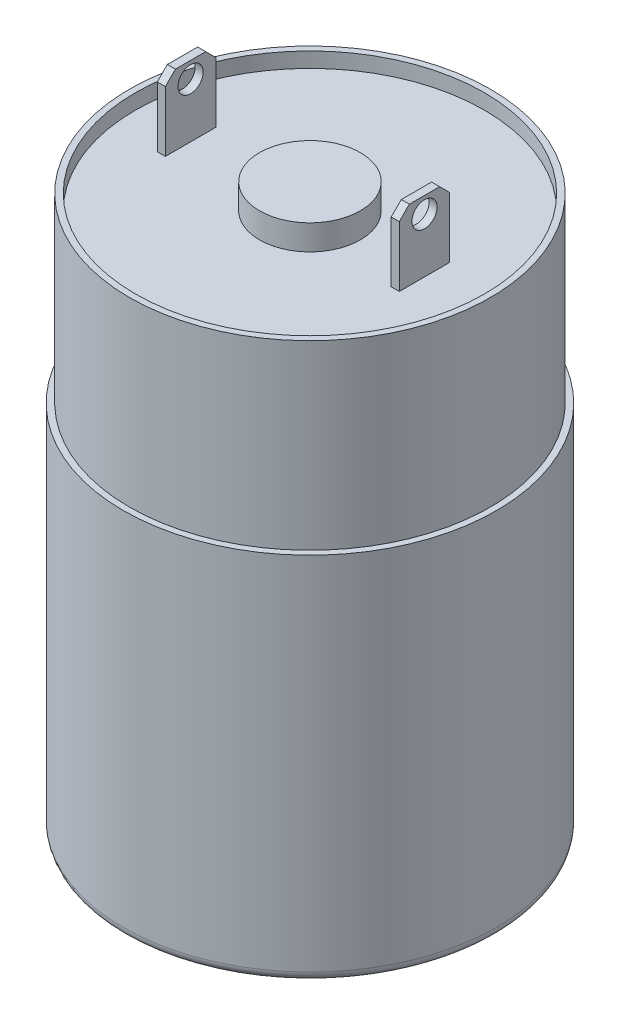
SolidWorks part; units mm, degrees
material "3.0205 (EN-AW 1200)"
ref_plane "Alzado" through (0, 0, 0) normal (0, 0, 1) x (1, 0, 0)
ref_plane "Planta" through (0, 0, 0) normal (0, 1, 0) x (1, 0, 0)
ref_plane "Vista lateral" through (0, 0, 0) normal (1, 0, 0) x (0, 0, -1)
sketch "Croquis1" plane through (0, 0, 0) normal (0, 1, 0) x (1, 0, 0)
  circle A0 centre (0, 0) radius 18.5
  dimension "D1" = 37
extrude "Saliente-Extruir1" add sketch "Croquis1" along normal mid plane 36.8
sketch "Croquis2" plane through (0, 18.4, 0) normal (0, 1, 0) x (1, 0, 0)
  circle A0 centre (0, 0) radius 17.9
  dimension "D1" = 35.8
extrude "Saliente-Extruir2" add sketch "Croquis2" along normal blind 18
sketch "Croquis3" plane through (0, 36.4, 0) normal (0, 1, 0) x (1, 0, 0)
  circle A0 centre (0, 0) radius 17.3
  dimension "D1" = 34.6
extrude "Cortar-Extruir1" cut sketch "Croquis3" against normal blind 1.5
sketch "Croquis4" plane through (0, 34.9, 0) normal (0, 1, 0) x (1, 0, 0)
  circle A0 centre (0, 0) radius 5
  dimension "D1" = 10
extrude "Saliente-Extruir3" add sketch "Croquis4" along normal blind 2.5
sketch "Croquis5" plane through (0, 34.9, 0) normal (0, 1, 0) x (1, 0, 0)
  line L0 (-11.8389, -2.5) -> (-11.8389, 2.5)
  line L2 (-11.8389, -2.5) -> (-12.6389, -2.5)
  line L3 (-11.8389, -2.5) -> (-11.8389, 2.5)
  line L4 (-11.8389, 2.5) -> (-12.6389, 2.5)
  line L5 (-12.6389, -2.5) -> (-12.6389, 2.5)
  point P2 (-11.8389, 0)
  dimension "D1" = 12.1
  dimension "D2" = 5
  dimension "D3" = 0.8
extrude "Saliente-Extruir4" add sketch "Croquis5" along normal blind 7 contours L5 L2 L0 L4
chamfer "Chaflán1" distance 1 angle 45 1 edges at (-12.2389, 41.9, 2.5)
chamfer "Chaflán2" distance 1 angle 45 1 edges at (-12.2389, 41.9, -2.5)
sketch "Croquis6" plane through (-11.8389, 0, 0) normal (1, 0, 0) x (0, 0, -1)
  line L0 (-1.5, 41.9) -> (1.5, 41.9) construction
  circle A0 centre (0, 40.2855) radius 1.25
  point P2 (0, 0)
  point P5 (0, 41.9)
  dimension "D1" = 2.5
extrude "Cortar-Extruir2" cut sketch "Croquis6" against normal blind 7
pattern_linear "MatrizL1" count 2 spacing 23.2 along (1, 0, 0) of "Cortar-Extruir2", "Chaflán2", "Saliente-Extruir4", "Chaflán1"
fillet "Redondeo1" radius 1 1 edges at (0, -18.4, 18.5)
